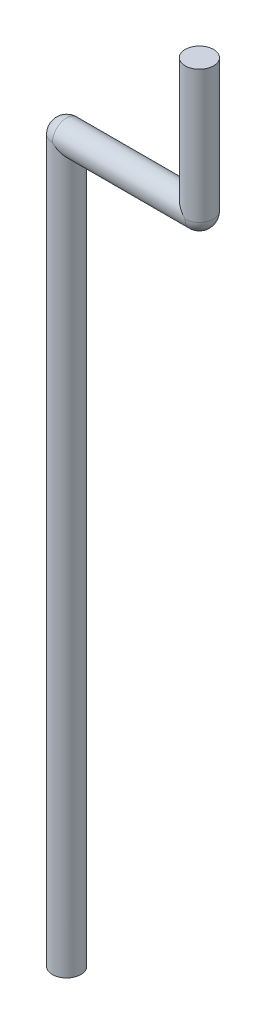
SolidWorks part; units mm, degrees
ref_plane "前视基准面" through (0, 0, 0) normal (0, 0, 1) x (1, 0, 0)
ref_plane "上视基准面" through (0, 0, 0) normal (0, 1, 0) x (1, 0, 0)
ref_plane "右视基准面" through (0, 0, 0) normal (1, 0, 0) x (0, 0, -1)
other "Configuration Table"
sketch "草图1" plane through (0, 0, 0) normal (0, 1, 0) x (1, 0, 0)
  circle A0 centre (0, 0) radius 0.75
  dimension "D1" = 1.5
extrude "凸台-拉伸1" add sketch "草图1" along normal blind 38
sketch "草图2" plane through (0, 0, 0) normal (0, 0, 1) x (1, 0, 0)
  line L2 (0.75, 38) -> (-0.75, 38) construction
  line L3 (0, 38.75) -> (0, 37.25)
  arc A1 (0, 37.25) -> (0, 38.75) centre (0, 38) ccw
revolve "旋转1" add sketch "草图2" angle 360 about L3
sketch "草图3" plane through (0, 0, 0) normal (1, 0, 0) x (0, 0, -1)
  line L0 (-0.75, 38) -> (0.75, 38) construction
  circle A0 centre (0, 38) radius 0.75
  dimension "D1" = 1.5
extrude "凸台-拉伸2" add sketch "草图3" along normal blind 7
sketch "草图4" plane through (7, 0, 0) normal (1, 0, 0) x (0, 0, -1)
  line L0 (0, 38.75) -> (0, 37.25)
  arc A0 (0, 37.25) -> (0, 38.75) centre (0, 38) ccw
  circle A1 centre (0, 38) radius 0.75 construction
  dimension "D1" = 0.75
revolve "旋转2" add sketch "草图4" angle 360 about L0
ref_plane "基准面1" through (0, 38, 0) normal (0, 1, 0) x (1, 0, 0)
sketch "草图5" plane through (0, 38, 0) normal (0, 1, 0) x (1, 0, 0)
  line L0 (7, 0.75) -> (7, -0.75) construction
  circle A0 centre (7, 0) radius 0.75
  dimension "D1" = 1.5
extrude "凸台-拉伸3" add sketch "草图5" along normal blind 7
